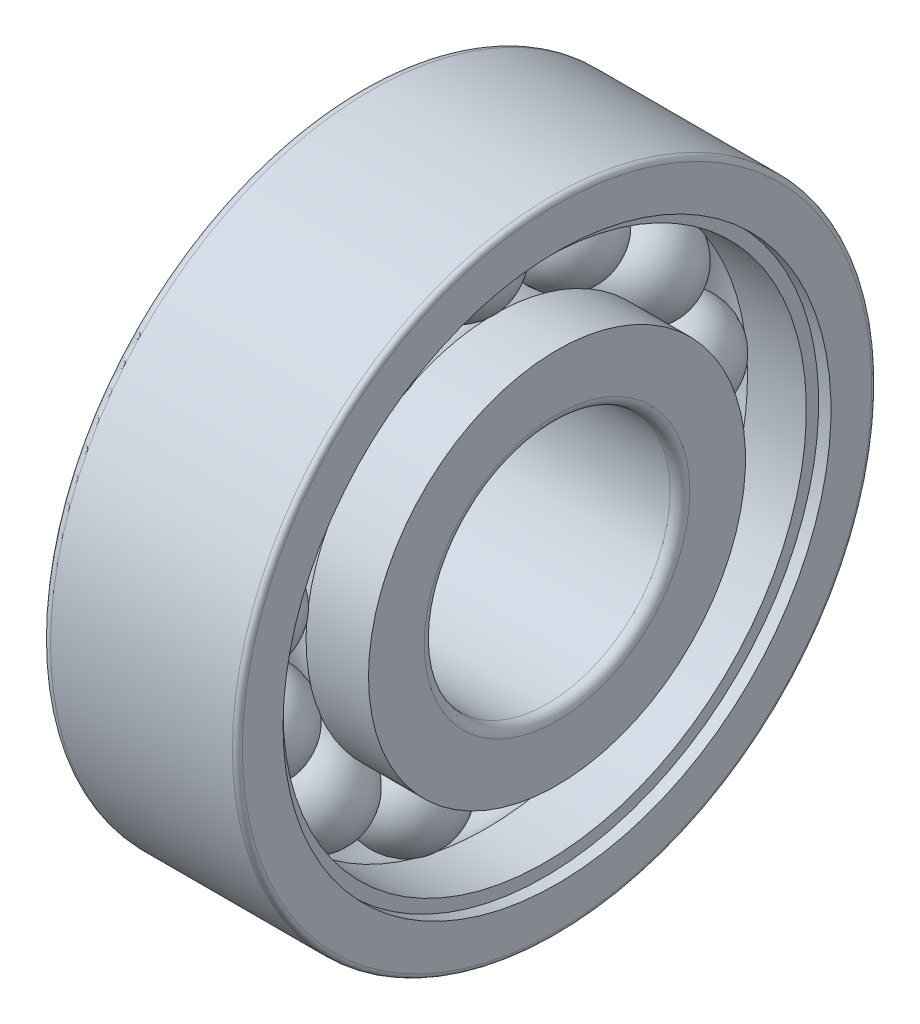
SolidWorks part; units mm, degrees
ref_plane "Front" through (0, 0, 0) normal (0, 0, 1) x (1, 0, 0)
ref_plane "Top" through (0, 0, 0) normal (0, 1, 0) x (1, 0, 0)
ref_plane "Right" through (0, 0, 0) normal (1, 0, 0) x (0, 0, -1)
sketch "Sketch1" plane through (0, 0, 0) normal (0, 0, 1) x (1, 0, 0)
  line L0 (-3.0919, 0) -> (2.899, 0) construction
  line L1 (-3.0919, 4.5) -> (2.899, 4.5) construction
  line L2 (-1, 4.5) -> (1, 4.5)
  arc A0 (-1, 4.5) -> (1, 4.5) centre (0, 4.5) ccw
  dimension "R" = 1
  dimension "D1" = 4.5
revolve "Revolve1" add sketch "Sketch1" angle 360 about L1
sketch "Sketch2" plane through (0, 0, 0) normal (0, 0, 1) x (1, 0, 0)
  line L0 (-2, 3.8333) -> (-0.7319, 3.8333)
  line L1 (2, 3.8333) -> (2, 2.5)
  line L2 (2, 2.5) -> (-2, 2.5)
  line L3 (-2, 2.5) -> (-2, 3.8333)
  line L4 (-2.9924, 0) -> (3.9982, 0) construction
  line L5 (-1.8743, 4.5) -> (3.1755, 4.5) construction
  line L7 (0.7319, 3.8333) -> (2, 3.8333)
  line L8 (-2, 6.2861) -> (-2, 1.454) construction
  arc A0 (-0.7319, 3.8333) -> (0.7319, 3.8333) centre (0, 4.5) ccw
  dimension "D1" = 4.5
  dimension "B" = 4
  dimension "D2" = 0.99
  dimension "d" = 5
  dimension "D3" = 7.6667
  dimension "T" = 4
  dimension "D6" = 2
revolve "Revolve2" add sketch "Sketch2" angle 360 about L4
sketch "Sketch3" plane through (0, 0, 0) normal (0, 0, 1) x (1, 0, 0)
  line L0 (-2, 5.1667) -> (-2, 6.5)
  line L1 (-2, 6.5) -> (2, 6.5)
  line L2 (2, 6.5) -> (2, 5.5717)
  line L3 (1.75, 5.3217) -> (0.5522, 5.3217)
  line L4 (-2.9924, 0) -> (3.4329, 0) construction
  line L6 (-1.7375, 4.5) -> (2.2712, 4.5) construction
  line L7 (-0.7319, 5.1667) -> (-2, 5.1667)
  line L8 (1.75, 5.3217) -> (1.75, 5.5717)
  line L9 (1.75, 5.5717) -> (2, 5.5717)
  arc A0 (0.5522, 5.3217) -> (-0.7319, 5.1667) centre (0, 4.5) ccw
  dimension "D1" = 4.5
  dimension "D4" = 0.99
  dimension "B" = 4
  dimension "DD" = 13
  dimension "D3" = 10.6433
  dimension "D5" = 10.3333
  dimension "D6" = 0.25
  dimension "D7" = 0.25
  dimension "D2" = 2
revolve "Revolve3" add sketch "Sketch3" angle 360 about L4
pattern_circular "Circular-Pattern1" count 13 over 360 about axis through (0, 0, 0) along (1, 0, 0) of "Revolve1"
fillet "Fillet1" radius 0.2 2 edges at (2, 0, 2.5) (-2, 0, 6.5)
fillet "Fillet2" radius 0.1 2 edges at (2, 0, 6.5) (-2, 0, 2.5)
equation "\"R@Sketch1\" =  ( \"DD@Sketch3\" - \"d@Sketch2\" )  / 8"
equation "\"D1@Sketch1\"=(\"d@Sketch2\"+\"DD@Sketch3\")/4"
equation "\"D1@Sketch2\"=(\"d@Sketch2\"+\"DD@Sketch3\")/4"
equation "\"D3@Sketch2\" =  \"d@Sketch2\"+  ( \"DD@Sketch3\" - \"d@Sketch2\" )  /3"
equation "\"D2@Sketch2\" =  ( \"DD@Sketch3\" - \"d@Sketch2\" )  / 8 - 0.01"
equation "\"D6@Sketch2\" = \"B@Sketch2\" / 2"
equation "\"B@Sketch3\" = \"B@Sketch2\""
equation "\"D2@Sketch3\" = \"B@Sketch3\" / 2"
equation "\"D1@Sketch3\"=(\"d@Sketch2\"+\"DD@Sketch3\")/4"
equation "\"D3@Sketch3\" = (  \"DD@Sketch3\" -  (\"DD@Sketch3\" - \"d@Sketch2\"  )  / 3 )  * 1.03"
equation "\"D5@Sketch3\" = \"DD@Sketch3\" -  (  \"DD@Sketch3\" - \"d@Sketch2\")  / 3"
equation "\"D6@Sketch3\" = \"d@Sketch2\" / 20"
equation "\"D7@Sketch3\"=\"D6@Sketch3\""
equation "\"D4@Sketch3\"=(\"DD@Sketch3\"-\"d@Sketch2\")/8-0.01"
equation "\"m@Circular-Pattern1\" = int( 3.14159265 / atn(\"R@Sketch1\" / sqr((\"d@Sketch2\"+\"DD@Sketch3\")/4 * (\"d@Sketch2\"+\"DD@Sketch3\")/4 - \"R@Sketch1\" *  \"R@Sketch1\")))-1"
